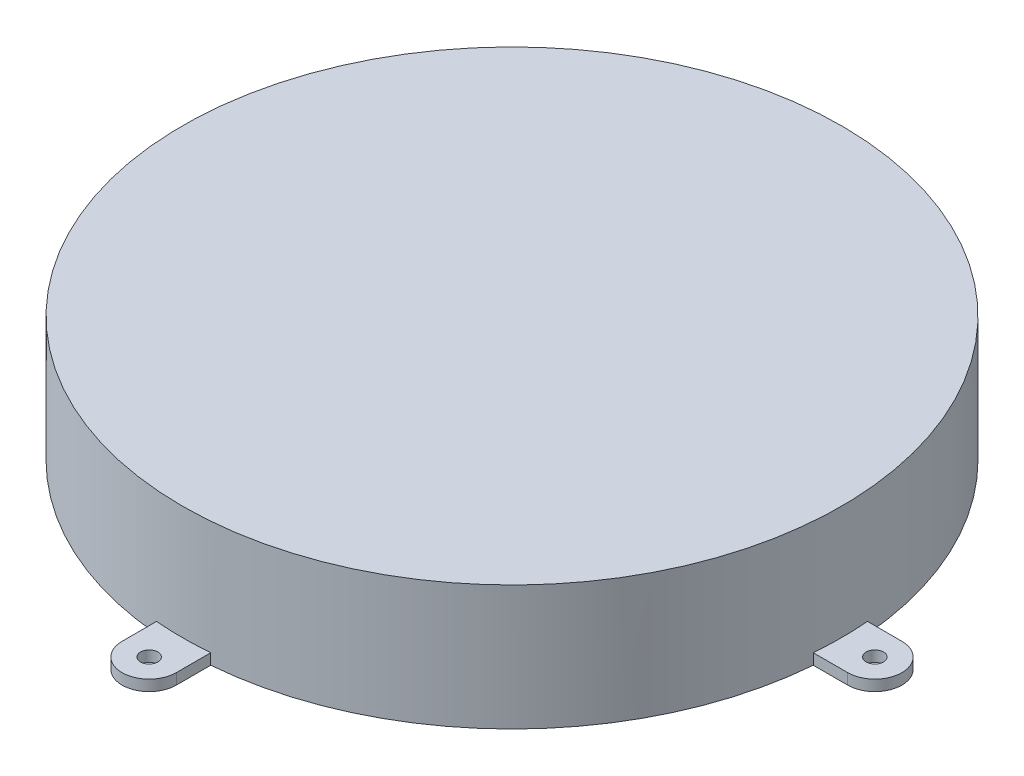
SolidWorks part; units mm, degrees
ref_plane "Front Plane" through (0, 0, 0) normal (0, 0, 1) x (1, 0, 0)
ref_plane "Top Plane" through (0, 0, 0) normal (0, 1, 0) x (1, 0, 0)
ref_plane "Right Plane" through (0, 0, 0) normal (1, 0, 0) x (0, 0, -1)
sketch "Sketch1" plane through (0, 0, 0) normal (0, 1, 0) x (1, 0, 0)
  circle A0 centre (0, 0) radius 59.75
  circle A1 centre (0, 0) radius 60.75
  dimension "D1" = 119.5
  dimension "D2" = 121.5
extrude "Boss-Extrude1" add sketch "Sketch1" along normal blind 21
sketch "Sketch2" plane through (0, 21, 0) normal (0, 1, 0) x (1, 0, 0)
  circle A1 centre (0, 0) radius 60.75
  circle A2 centre (0, 0) radius 60.75
  dimension "D1" = 0
extrude "Boss-Extrude2" add sketch "Sketch2" along normal blind 2
sketch "Sketch3" plane through (0, 0, 0) normal (0, 1, 0) x (1, 0, 0)
  line L0 (0, 85.9202) -> (0, -75.632) construction
  line L1 (-70.627, 0) -> (71.7392, 0) construction
  line L2 (5, 66.8939) -> (5, 60.5439)
  line L3 (5, 60.5439) -> (-5, 60.5439)
  line L4 (-5, 60.5439) -> (-5, 66.8939)
  line L5 (0, 71.8939) -> (-15.9172, 71.8939) construction
  line L6 (0, 60.5439) -> (-17.5017, 60.5439) construction
  line L7 (60.5439, 5) -> (66.8939, 5)
  line L8 (66.8939, -5) -> (60.5439, -5)
  line L9 (60.5439, -5) -> (60.5439, 5)
  line L10 (5, -60.5439) -> (5, -66.8939)
  line L11 (-5, -66.8939) -> (-5, -60.5439)
  line L12 (-5, -60.5439) -> (5, -60.5439)
  line L13 (-60.5439, -5) -> (-66.8939, -5)
  line L14 (-66.8939, 5) -> (-60.5439, 5)
  line L15 (-60.5439, 5) -> (-60.5439, -5)
  arc A0 (-5, 66.8939) -> (5, 66.8939) centre (0, 66.8939) cw
  circle A1 centre (0, 0) radius 60.75 construction
  circle A2 centre (0, 66.8939) radius 1.6
  circle A3 centre (66.8939, 0) radius 1.6
  arc A4 (66.8939, 5) -> (66.8939, -5) centre (66.8939, 0) cw
  circle A5 centre (0, -66.8939) radius 1.6
  arc A6 (5, -66.8939) -> (-5, -66.8939) centre (0, -66.8939) cw
  circle A7 centre (-66.8939, 0) radius 1.6
  arc A8 (-66.8939, -5) -> (-66.8939, 5) centre (-66.8939, 0) cw
  point P17 (0, 0)
  point P38 (0, 0)
  dimension "D1" = 10
  dimension "D2" = 3.2
  dimension "D3" = 11.35
  dimension "D4" = 4
extrude "Boss-Extrude3" add sketch "Sketch3" along normal blind 2
